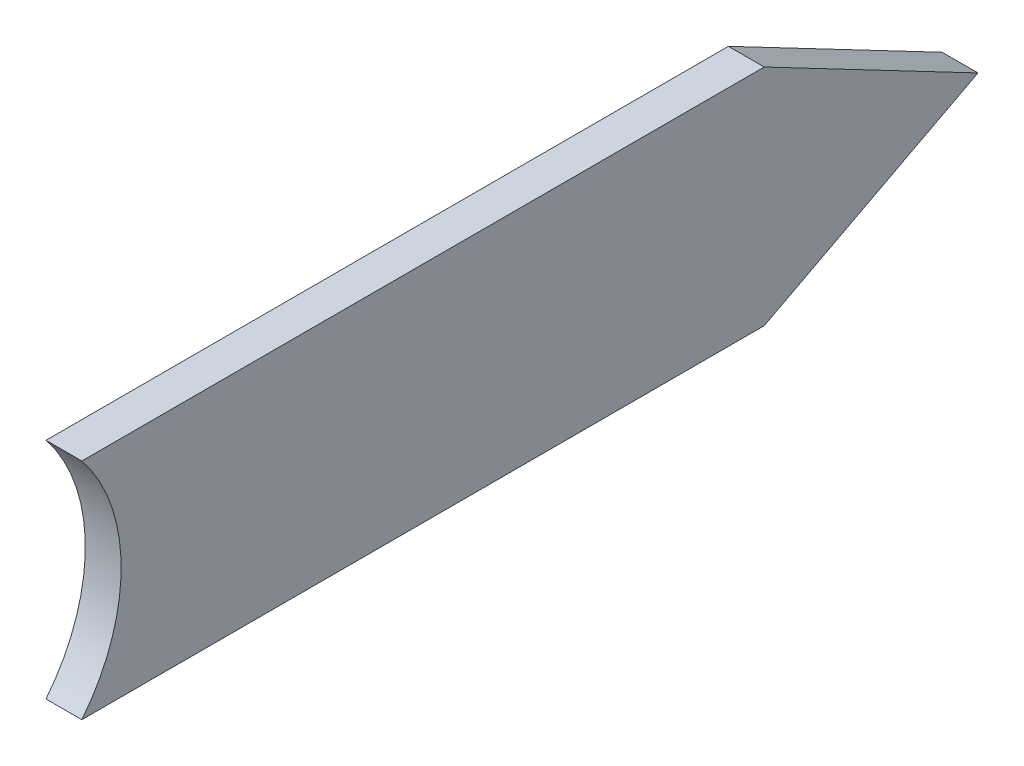
SolidWorks part; units mm, degrees
material "ASTM A36 Steel"
ref_plane "Front Plane" through (0, 0, 0) normal (0, 0, 1) x (1, 0, 0)
ref_plane "Top Plane" through (0, 0, 0) normal (0, 1, 0) x (1, 0, 0)
ref_plane "Right Plane" through (0, 0, 0) normal (1, 0, 0) x (0, 0, -1)
sketch "Sketch1" plane through (0, 0, 0) normal (1, 0, 0) x (0, 0, -1)
  line L0 (100, 0) -> (52.2936, 25)
  line L1 (-100, -25) -> (52.2936, -25)
  line L3 (-100, 25) -> (52.2936, 25)
  line L7 (100, 0) -> (52.2936, -25)
  arc A0 (-100, 25) -> (-100, -25) centre (-131.225, 0) cw
  point P0 (0, 0)
  dimension "D2" = 40
  dimension "D1" = 50
extrude "Boss-Extrude1" add sketch "Sketch1" along normal blind 8
